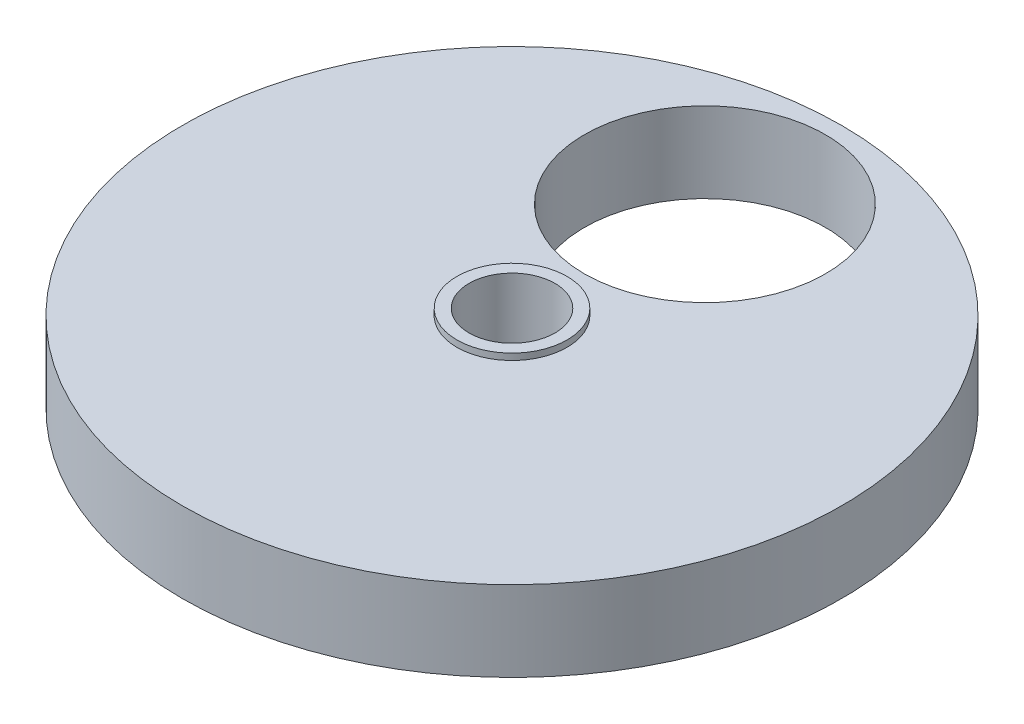
SolidWorks part; units mm, degrees
ref_plane "Front Plane" through (0, 0, 0) normal (0, 0, 1) x (1, 0, 0)
ref_plane "Top Plane" through (0, 0, 0) normal (0, 1, 0) x (1, 0, 0)
ref_plane "Right Plane" through (0, 0, 0) normal (1, 0, 0) x (0, 0, -1)
sketch "Sketch1" plane through (0, 0, 0) normal (0, 1, 0) x (1, 0, 0)
  circle A0 centre (0, 0) radius 20.5
  dimension "D1" = 41
extrude "Boss-Extrude1" add sketch "Sketch1" along normal blind 5
sketch "Sketch2" plane through (0, 5, 0) normal (0, 1, 0) x (1, 0, 0)
  circle A0 centre (0, 0) radius 2.675
  dimension "D1" = 5.35
extrude "Cut-Extrude1" cut sketch "Sketch2" against normal blind 5
sketch "Sketch3" plane through (0, 5, 0) normal (0, 1, 0) x (1, 0, 0)
  circle A0 centre (0, 0) radius 3.425
  circle A1 centre (0, 0) radius 2.675
  dimension "D1" = 5.35
  dimension "D2" = 6.85
extrude "Boss-Extrude2" add sketch "Sketch3" along normal blind 0.4
sketch "Sketch5" plane through (0, 5, 0) normal (0, 1, 0) x (1, 0, 0)
  circle A0 centre (0, 12) radius 7.5
  dimension "D1" = 15
  dimension "D2" = 12
extrude "Cut-Extrude3" cut sketch "Sketch5" against normal blind 5
